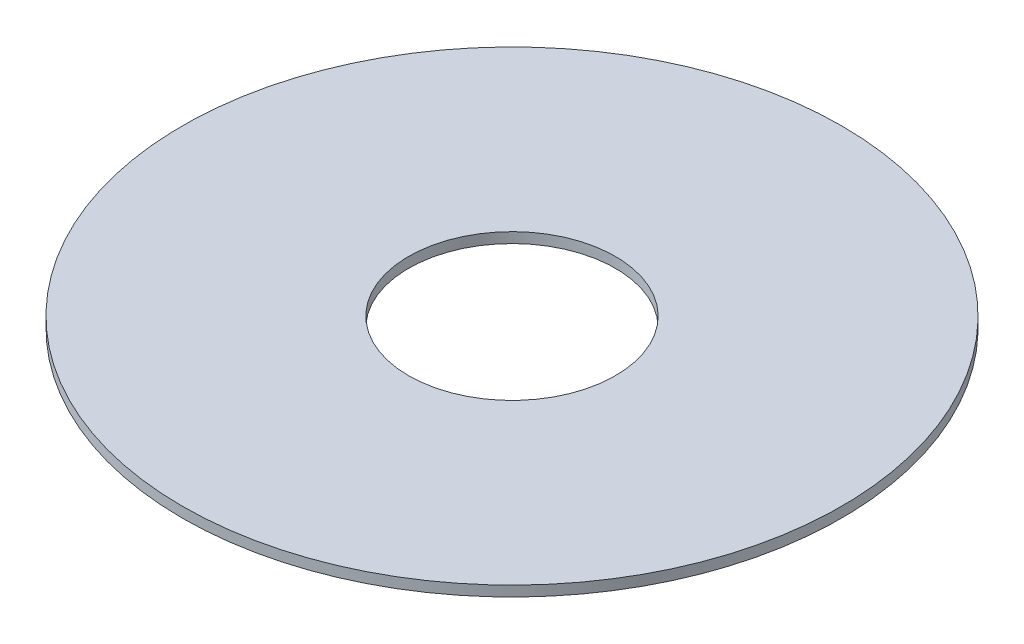
SolidWorks part; units mm, degrees
ref_plane "Front Plane" through (0, 0, 0) normal (0, 0, 1) x (1, 0, 0)
ref_plane "Top Plane" through (0, 0, 0) normal (0, 1, 0) x (1, 0, 0)
ref_plane "Right Plane" through (0, 0, 0) normal (1, 0, 0) x (0, 0, -1)
sketch "Sketch1" plane through (0, 0, 0) normal (0, 1, 0) x (1, 0, 0)
  circle A0 centre (0, 0) radius 25.4
  circle A1 centre (0, 0) radius 80.9625
  dimension "D1" = 161.925
  dimension "D2" = 50.8
extrude "Boss-Extrude1" add sketch "Sketch1" along normal blind 2.54
